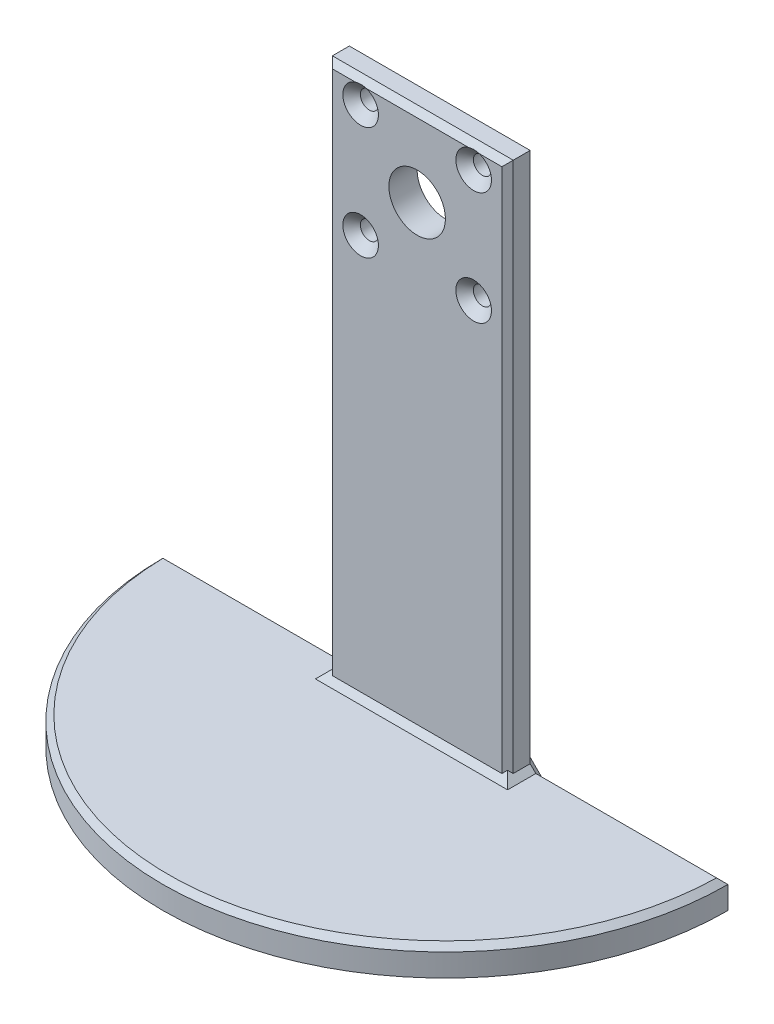
SolidWorks part; units mm, degrees
ref_plane "Ebene vorne" through (0, 0, 0) normal (0, 0, 1) x (1, 0, 0)
ref_plane "Ebene oben" through (0, 0, 0) normal (0, 1, 0) x (1, 0, 0)
ref_plane "Ebene rechts" through (0, 0, 0) normal (1, 0, 0) x (0, 0, -1)
sketch "Skizze1" plane through (0, 0, 0) normal (0, 0, 1) x (1, 0, 0)
  line L5 (16, -13.3867) -> (16, 7.5971)
  line L6 (16, 7.5971) -> (16, 14)
  line L7 (16, 14) -> (-16, 14)
  line L8 (-16, 14) -> (-16, 4.5595)
  line L9 (-16, 4.5595) -> (-16, -16.4243)
  line L10 (-16, -16.4243) -> (-16, -86)
  line L11 (16, -13.3867) -> (16, -86)
  line L12 (16, -86) -> (-16, -86)
  line L13 (0, 14) -> (0, -86) construction
  circle A0 centre (0, 0) radius 5
  circle A1 centre (10, -10) radius 1.6
  circle A2 centre (-10, -10) radius 1.6
  circle A3 centre (-10, 10) radius 1.6
  circle A4 centre (10, 10) radius 1.6
  dimension "D2" = 3.2
  dimension "D13" = 10
  dimension "D1" = 100
  dimension "D3" = 32
  dimension "D4" = 10
  dimension "D5" = 10
  dimension "D6" = 10
  dimension "D7" = 10
  dimension "D8" = 10
  dimension "D9" = 10
  dimension "D10" = 10
  dimension "D11" = 10
  dimension "D12" = 14
extrude "Aufsatz-Linear austragen1" add sketch "Skizze1" along normal blind 5
sketch "Skizze2" plane through (0, -86, 0) normal (0, -1, 0) x (-1, 0, 0)
  line L0 (0, 0) -> (50.0761, 0) construction
  line L1 (50.0761, 0) -> (-50, 0)
  arc A0 (-50, 0) -> (50, 0) centre (0, 0) ccw
  line M3 (-16, 0) -> (-16, -5)
  line M4 (-16, -5) -> (16, -5)
  line M5 (16, -5) -> (16, 0)
  dimension "D1" = 100
extrude "Aufsatz-Linear austragen2" add sketch "Skizze2" against normal blind 5 contours L1 A0 M5 M4 M3
chamfer "Fase1" distance 1 angle 45 8 edges at (-16, -33.5, 0) (16, -33.5, 0) (0, -81, 50) (-33, -81, 0) (-16, -81, 2.5) (0, -81, 5) (16, -81, 2.5) (33, -81, 0)
chamfer "Fase2" distance 1 angle 45 3 edges at (16, -33, 5) (0, 14, 5) (-16, -33, 5)
chamfer "Fase3" distance 1 angle 45 1 edges at (0, 14, 0)
hole_wizard "Formsenkung für M3 Linsensenkschraube mit Schlitz1" positions "Skizze5" profile "Skizze4" countersink size "M3" standard "DIN" end condition through all
sketch "Skizze5" plane through (0, 0, 5) normal (0, 0, 1) x (1, 0, 0)
  point P0 (-10, 10)
  point P3 (10, 10)
  point P6 (-10, -10)
  point P9 (10, -10)
sketch "Skizze4" plane through (-10, 10, 5) normal (1, 0, 0) x (0, -1, 0)
  line L0 (0, 0) -> (0, 5)
  line L1 (0, 5) -> (1.6, 5)
  line L2 (1.6, 5) -> (1.6, 1.55)
  line L3 (1.6, 1.55) -> (3.15, 0)
  line L5 (3.15, 0) -> (0, 0)
  line L6 (-1.6, 1.55) -> (-3.15, 0) construction
  line L11 (0, -6.35) -> (0, 107.95) construction
  dimension "Bohrerdurchmesser" = 3.2
  dimension "Bohrungstiefe" = 5
  dimension "Senkdurchmesser (Oben)" = 6.3
  dimension "Senkwinkel (Oben)" = 90
